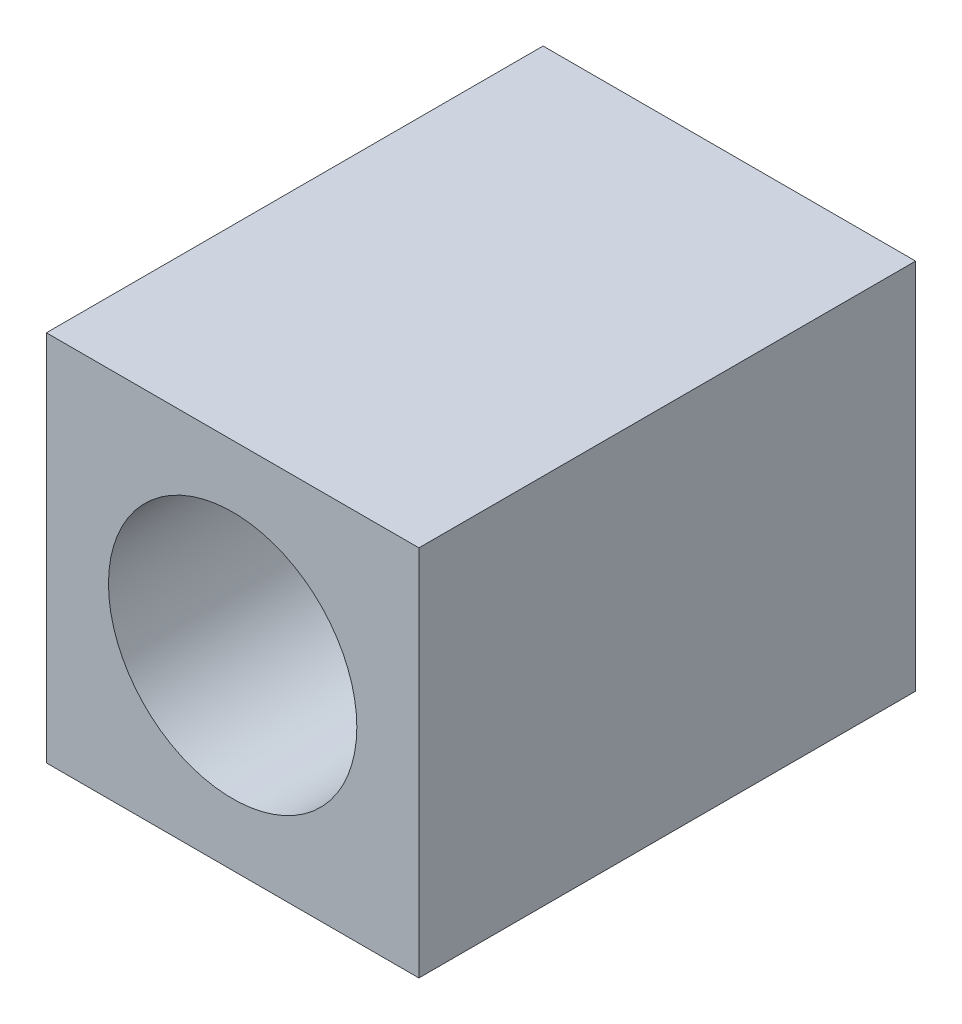
SolidWorks part; units mm, degrees
ref_plane "前视基准面" through (0, 0, 0) normal (0, 0, 1) x (1, 0, 0)
ref_plane "上视基准面" through (0, 0, 0) normal (0, 1, 0) x (1, 0, 0)
ref_plane "右视基准面" through (0, 0, 0) normal (1, 0, 0) x (0, 0, -1)
sketch "草图1" plane through (0, 0, 0) normal (0, 0, 1) x (1, 0, 0)
  line L1 (-3, -3) -> (3, -3)
  line L2 (-3, -3) -> (-3, 3)
  line L3 (-3, 3) -> (3, 3)
  line L4 (3, -3) -> (3, 3)
  line L5 (-3, -3) -> (3, 3) construction
  line L6 (-3, 3) -> (3, -3) construction
  point P0 (0, 0)
  dimension "D1" = 6
extrude "凸台-拉伸1" add sketch "草图1" along normal blind 8
sketch "草图2" plane through (0, 0, 8) normal (0, 0, 1) x (1, 0, 0)
  circle A0 centre (0, 0) radius 2
  dimension "D1" = 4
extrude "切除-拉伸1" cut sketch "草图2" against normal through all
